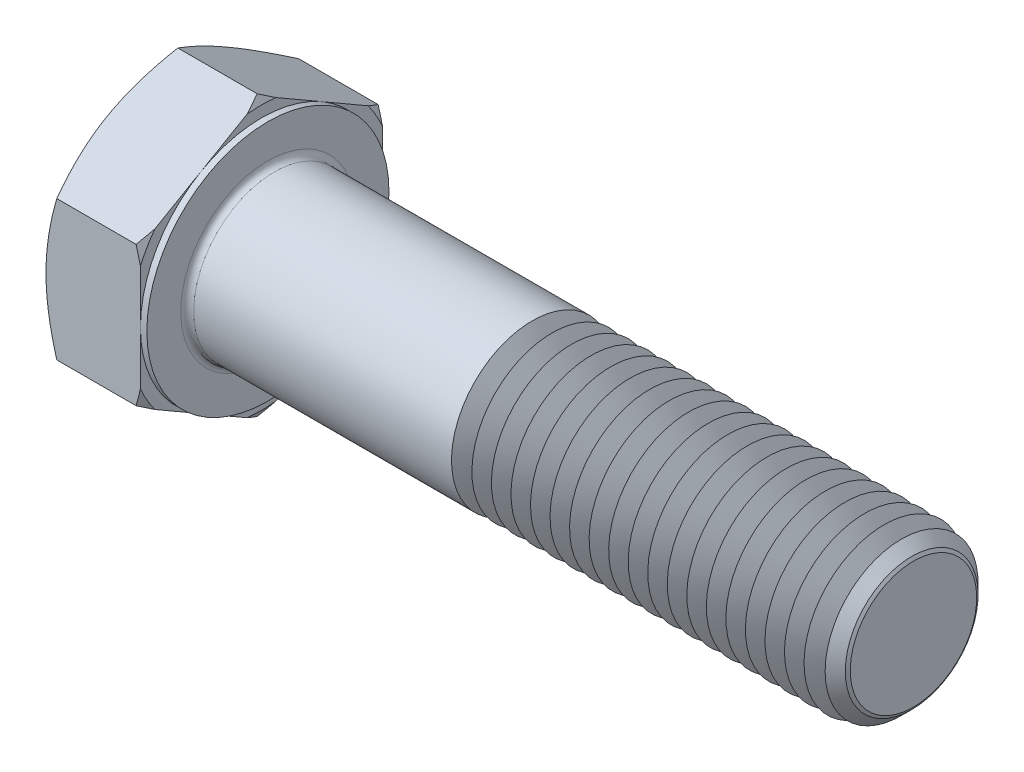
SolidWorks part; units mm, degrees
extrude "基体-拉伸" add sketch "草图1" along normal blind 12.5
sketch "草图1" plane through (0, 0, 0) normal (1, 0, 0) x (0, 0, -1)
  line L0 (15, 8.6603) -> (15, -8.6603)
  line L1 (-15, 8.6603) -> (-15, -8.6603)
  line L2 (15, -8.6603) -> (0, -17.3205)
  line L3 (0, -17.3205) -> (-15, -8.6603)
  line L4 (15, 8.6603) -> (0, 17.3205)
  line L5 (0, 17.3205) -> (-15, 8.6603)
  dimension "s" = 30
  dimension "D2" = 120
  dimension "D3" = 15
  dimension "D4" = 15
  dimension "D5" = 15
revolve "切除-旋转1" cut sketch "草图3" angle 360 about L6
sketch "草图3" plane through (0, 0, 0) normal (0, 0, 1) x (1, 0, 0)
  line L0 (0, 15) -> (4.2265, 22.3205)
  line L1 (0, 17.3205) -> (0, 8.6603) construction
  line L2 (4.2265, 22.3205) -> (4.2265, 27.3205)
  line L3 (4.2265, 27.3205) -> (-10, 27.3205)
  line L4 (-10, 27.3205) -> (-10, 15)
  line L5 (-10, 15) -> (0, 15)
  line L6 (0, 0) -> (99.06, 0) construction
  line L7 (12.5, 17.3205) -> (0, 17.3205) construction
  dimension "D1" = 15
  dimension "D2" = 5
  dimension "D3" = 10
  dimension "D4" = 5
  dimension "Head_ch_ang" = 30
ref_plane "前视" through (0, 0, 0) normal (0, 0, 1) x (1, 0, 0)
ref_plane "上视" through (0, 0, 0) normal (0, 1, 0) x (1, 0, 0)
ref_plane "右视" through (0, 0, 0) normal (1, 0, 0) x (0, 0, -1)
sketch "草图2" plane through (0, 0, 0) normal (0, 0, 1) x (1, 0, 0)
  line L0 (0, 8.6603) -> (0, -8.6603) construction
  line L1 (0, 0) -> (92.5, 0)
  line L2 (0, 0) -> (0, 10)
  line L3 (0, 10) -> (27.8072, 10)
  line L4 (92.5, 0) -> (92.5, 7.835)
  line L5 (12.5, 17.3205) -> (12.5, 8.6603) construction
  line L7 (0, 0) -> (96.52, 0) construction
  line L8 (92.5, -7.835) -> (27.8072, -10) construction
  line L9 (0, -10) -> (27.8072, -10) construction
  line L10 (15, 15.24) -> (15, -1.27) construction
  line L11 (46.5, 15.24) -> (46.5, -1.27) construction
  line L12 (12.5, 8.6603) -> (12.5, -8.6603) construction
  line L13 (27.8072, 10) -> (92.5, 10)
  line L14 (92.5, 10) -> (92.5, 7.835)
revolve "凸台-旋转1" add sketch "草图2" angle 360 about L7
cosmetic thread "螺旋线1" parameters "Thread_length"=46, "Thread_minor"=15.67
sketch "草图5" plane through (0, 0, 0) normal (0, 0, 1) x (1, 0, 0)
  line L0 (12.5, 15) -> (8.2735, 22.3205)
  line L1 (12.5, 17.3205) -> (12.5, 8.6603) construction
  line L2 (8.2735, 22.3205) -> (8.2735, 27.3205)
  line L3 (8.2735, 27.3205) -> (18.2735, 27.3205)
  line L4 (18.2735, 27.3205) -> (18.2735, 15)
  line L5 (18.2735, 15) -> (12.5, 15)
  line L7 (12.5, 17.3205) -> (1.3397, 17.3205) construction
  line L8 (0, 0) -> (99.06, 0) construction
  line L9 (0, 0) -> (99.06, 0) construction
  dimension "D1" = 15
  dimension "D2" = 5
  dimension "D3" = 10
  dimension "D4" = 5
revolve "切除-旋转2" cut sketch "草图5" angle 360 about L8
sketch "草图4" plane through (0, 0, 0) normal (0, 0, 1) x (1, 0, 0)
  line L1 (12.5, 17.3205) -> (12.5, 8.6603) construction
  line L2 (12.5, 15) -> (11.7, 15)
  line L3 (12.5, 15) -> (12.5, 27.3205)
  line L4 (12.5, 27.3205) -> (11.7, 27.3205)
  line L5 (0, 0) -> (95.25, 0) construction
  line L6 (0, 0) -> (96.52, 0) construction
  line L7 (11.7, 15) -> (11.7, 27.3205)
  line L8 (11.1603, 17.3205) -> (1.3397, 17.3205) construction
  dimension "D2" = 10
  dimension "D1" = 30
revolve "切除-旋转3" cut sketch "草图4" angle 360 about L5
chamfer "倒角" distance 2 angle 45 1 edges at (92.5, 0, 10)
fillet "圆角" radius 0.8 1 edges at (12.5, 0, -10)
sketch "草图6" plane through (0, 0, 0) normal (0, 0, 1) x (1, 0, 0)
  line L0 (46.5, -7.835) -> (45.25, -10)
  line L1 (46.5, -7.835) -> (47.75, -10)
  line L2 (47.75, -10) -> (47.75, -12.5)
  line L3 (-3.175, 0) -> (5.1513, 0) construction
  line L5 (47.75, -12.5) -> (45.25, -12.5)
  line L6 (45.25, -12.5) -> (45.25, -10)
  dimension "Thread_minor" = 15.67
  dimension "Diameter" = 20
  dimension "Start" = 46.5
revolve "切除-旋转4" cut sketch "草图6" angle 360 about L3
pattern_linear "阵列(线性)1" count 20 spacing 2.4211 along (1, 0, 0) of "切除-旋转4"
equation "\"D3@草图1\" = \"s@草图1\" / 2"
equation "\"D4@草图1\" = \"D3@草图1\""
equation "\"D5@草图1\" = \"D4@草图1\""
equation "\"Thread_minor@螺旋线1\" = \"Minor_dia@草图2\""
equation "\"D1@草图3\" = \"s@草图1\" / 2"
equation "\"D1@草图5\" = \"s@草图1\" / 2"
equation "\"Head_ch_ang@草图5\" = \"Head_ch_ang@草图3\""
equation "\"D1@草图4\" = \"s@草图1\""
equation "\"Thread_length@螺旋线1\" = ((sgn( (\"l@草图2\" - \"p@草图2\" ) - \"h@草图2\" )-1)*( (\"l@草图2\" - \"p@草图2\" ) - \"h@草图2\" ))/-2+ \"h@草图2\""
equation "\"Thread_minor@草图6\" = \"Minor_dia@草图2\""
equation "\"Diameter@草图6\" = \"m@草图2\""
equation "\"Overcut@草图6\" = \"m@草图2\" * 1.25"
equation "\"Start@草图6\" = \"k@基体-拉伸\" + \"l@草图2\" - \"Thread_length@螺旋线1\"  '---Non-countersunk---"
equation "\"Num_threads@阵列(线性)1\" = int( \"Thread_length@螺旋线1\" / \"p@草图2\" + 0.999 )  + 1"
equation "\"Advance@阵列(线性)1\" = \"Thread_length@螺旋线1\" /  (\"Num_threads@阵列(线性)1\" - 1) 'relax it"
equation "\"Num_threads@阵列(线性)1\" = \"Num_threads@阵列(线性)1\" - sgn( \"Num_threads@阵列(线性)1\" - 1) '---chamfered tips only---"
equation "\"Minor_dia@草图2\" = \"m@草图2\"-\"p@草图2\" * 1.732"
equation "\"D1@倒角\" = \"p@草图2\"*0.8"
